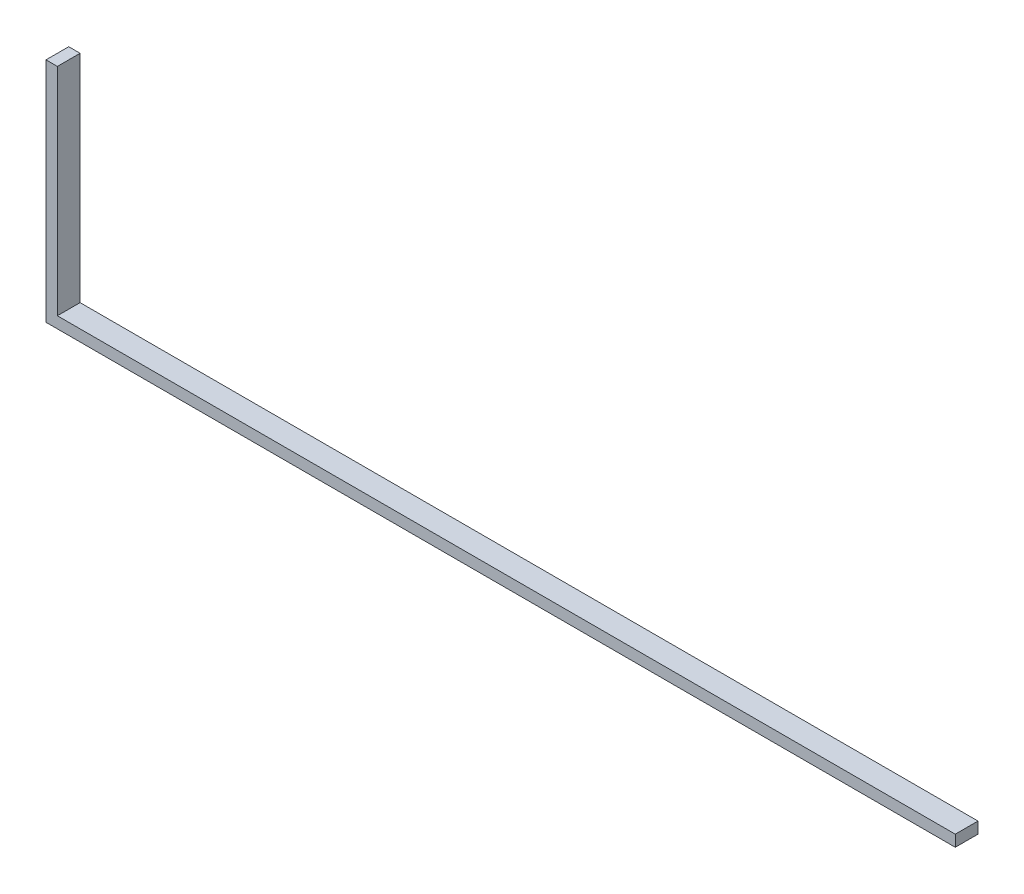
SolidWorks part; units mm, degrees
ref_plane "前视基准面" through (0, 0, 0) normal (0, 0, 1) x (1, 0, 0)
ref_plane "上视基准面" through (0, 0, 0) normal (0, 1, 0) x (1, 0, 0)
ref_plane "右视基准面" through (0, 0, 0) normal (1, 0, 0) x (0, 0, -1)
sketch "草图1" plane through (0, 0, 0) normal (0, 0, 1) x (1, 0, 0)
  line L0 (0, 1000) -> (0, 0)
  line L1 (0, 0) -> (4000, 0)
  line L2 (4000, 0) -> (4000, 50)
  line L3 (4000, 50) -> (50, 50)
  line L4 (50, 50) -> (50, 1000)
  line L5 (50, 1000) -> (0, 1000)
  dimension "D1" = 50
  dimension "D2" = 50
  dimension "D3" = 4000
  dimension "D4" = 1000
extrude "凸台-拉伸1" add sketch "草图1" along normal blind 100
